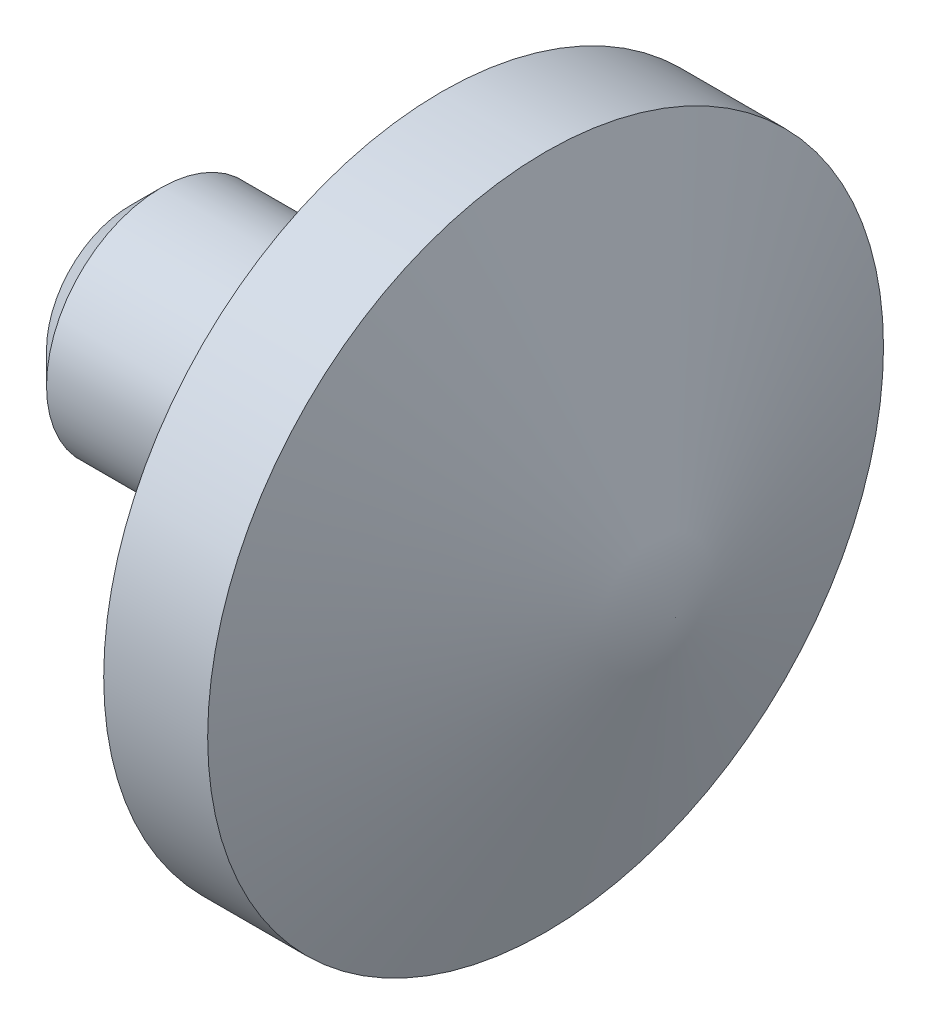
SolidWorks part; units mm, degrees
ref_plane "Plan de face" through (0, 0, 0) normal (0, 0, 1) x (1, 0, 0)
ref_plane "Plan de dessus" through (0, 0, 0) normal (0, 1, 0) x (1, 0, 0)
ref_plane "Plan de droite" through (0, 0, 0) normal (1, 0, 0) x (0, 0, -1)
sketch "Sketch1" plane through (0, 0, 0) normal (0, 0, 1) x (1, 0, 0)
  line L2 (2.25, 0) -> (1, 3.25)
  line L3 (1, 3.25) -> (0, 3.25)
  line L4 (0, 3.25) -> (0, 1.1)
  line L5 (0, 0) -> (-3, 0)
  line L6 (-3, 0) -> (-3, 1.1)
  line L7 (-3, 1.1) -> (0, 1.1)
  line L8 (0, 0) -> (2.25, 0)
  point P7 (-3, 1.1)
  point P10 (-3.0311, 1.1)
  point P11 (0, 0)
  point P12 (-3, 1.1)
  point P13 (-3, 1.0699)
  dimension "D1" = 1
  dimension "D2" = 3
  dimension "D3" = 3.25
  dimension "D4" = 3
  dimension "D5" = 1.1
  dimension "D6" = 2.25
  dimension "D9" = 1.1
revolve "Revolve1" add sketch "Sketch1" angle 360 about L5
cosmetic thread "Cosmetic Thread4" parameters "D1"=3, "D2"=1.6
chamfer "Chamfer2" distance 0.3 angle 45 1 edges at (-3, 0, -1.1)
